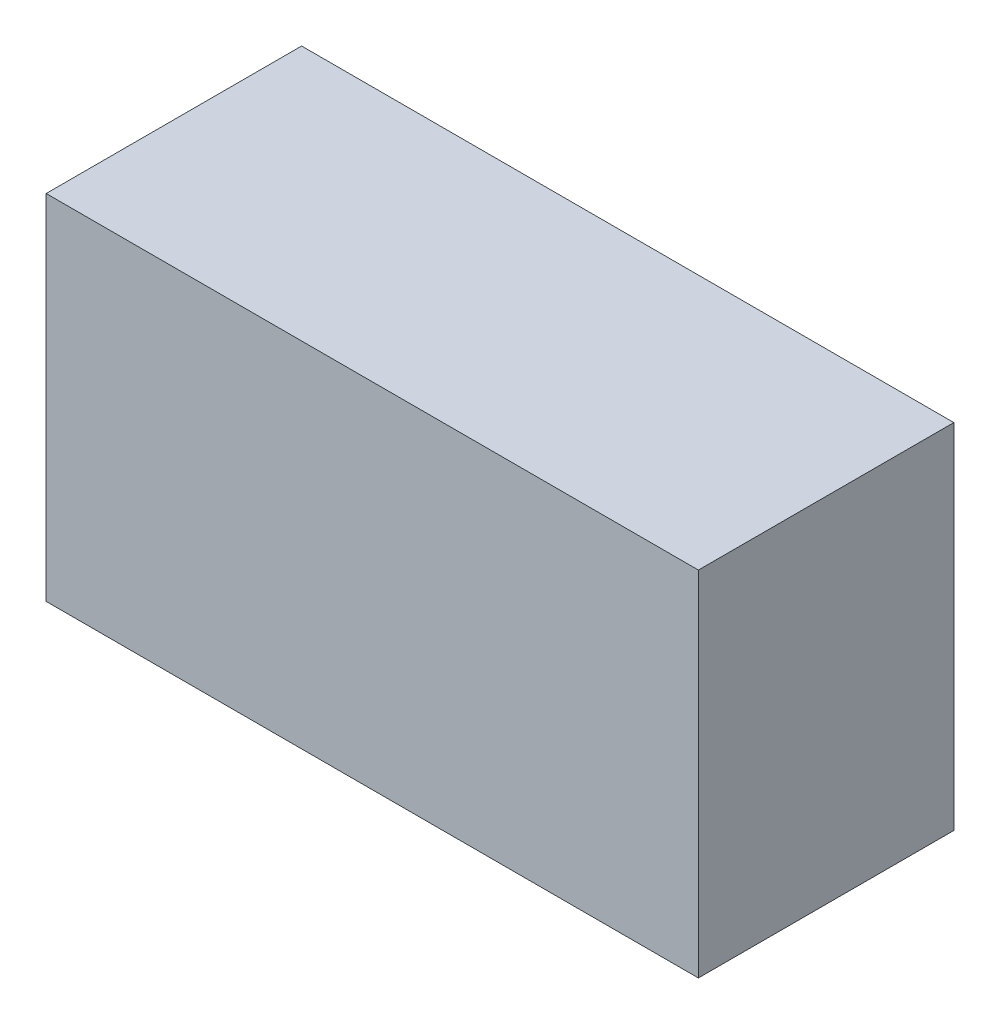
SolidWorks part; units mm, degrees
ref_plane "Front Plane" through (0, 0, 0) normal (0, 0, 1) x (1, 0, 0)
ref_plane "Top Plane" through (0, 0, 0) normal (0, 1, 0) x (1, 0, 0)
ref_plane "Right Plane" through (0, 0, 0) normal (1, 0, 0) x (0, 0, -1)
sketch "Sketch1" plane through (0, 0, 0) normal (0, 0, 1) x (1, 0, 0)
  line L2 (0, 0) -> (60, 0)
  line L3 (0, 0) -> (0, 32.5)
  line L4 (0, 32.5) -> (60, 32.5)
  line L5 (60, 0) -> (60, 32.5)
  dimension "D1" = 60
  dimension "D2" = 32.5
extrude "Boss-Extrude1" add sketch "Sketch1" along normal blind 23.5
